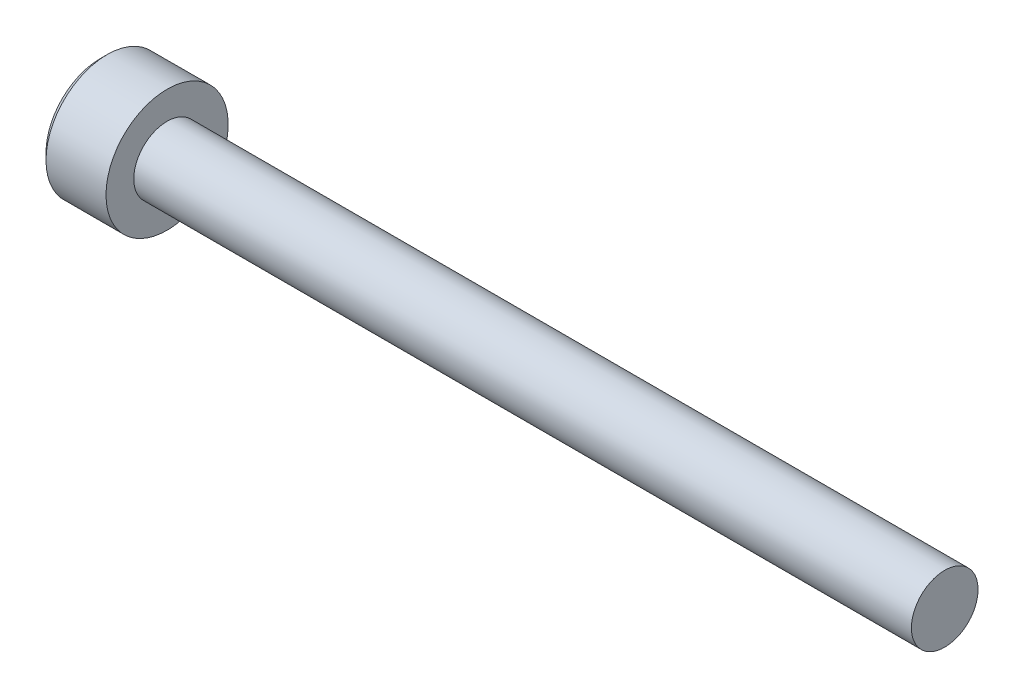
SolidWorks part; units mm, degrees
ref_plane "Front Plane" through (0, 0, 0) normal (0, 0, 1) x (1, 0, 0)
ref_plane "Top Plane" through (0, 0, 0) normal (0, 1, 0) x (1, 0, 0)
ref_plane "Right Plane" through (0, 0, 0) normal (1, 0, 0) x (0, 0, -1)
sketch "Sketch1" plane through (0, 0, 0) normal (0, 0, 1) x (1, 0, 0)
  line L0 (-3, 0) -> (35, 0) construction
  line L1 (-3, 0) -> (35, 0)
  line L2 (0, 1.5) -> (0, 2.75)
  line L3 (0, 2.75) -> (-3, 2.75)
  line L4 (-3, 0) -> (-3, 2.75)
  line L5 (0, 1.5) -> (35, 1.5)
  line L8 (35, 1.5) -> (35, 0)
  dimension "M" = 3
  dimension "A" = 5.5
  dimension "E" = 3
  dimension "BL" = 35
revolve "Revolve1" add sketch "Sketch1" angle 360 about L0
cosmetic thread "Thread101" parameters "L_s"=35, "TD_s"=2.459
sketch "Sketch2" plane through (-3, 0, 0) normal (-1, 0, 0) x (0, 0, 1)
  line L1 (0, 1.4434) -> (-1.25, 0.7217)
  line L2 (-1.25, 0.7217) -> (-1.25, -0.7217)
  line L3 (-1.25, -0.7217) -> (0, -1.4434)
  line L4 (0, -1.4434) -> (1.25, -0.7217)
  line L5 (1.25, -0.7217) -> (1.25, 0.7217)
  line L6 (1.25, 0.7217) -> (0, 1.4434)
  circle A0 centre (0, 0) radius 1.25 construction
  dimension "B" = 2.5
extrude "Cut-Extrude1" cut sketch "Sketch2" against normal blind 1.3
sketch "Sketch6" plane through (0, 0, 0) normal (0, 0, 1) x (1, 0, 0)
  line L0 (-1.7, 0) -> (-9.4368, 0) construction
  line L1 (-1.7, 0) -> (-1.7, 1.25)
  line L2 (-1.7, 1.25) -> (-0.9783, 0)
  line L3 (-0.9783, 0) -> (-1.7, 0)
  dimension "FIX_3" = 120
  dimension "FIX_6" = 2.5
  dimension "FIX_5" = 1.7
revolve "Cut-Revolve1" cut sketch "Sketch6" angle 360 about L0
chamfer "Chamfer1" distance 0.3 1 edges at (-3, 0, 2.75)
